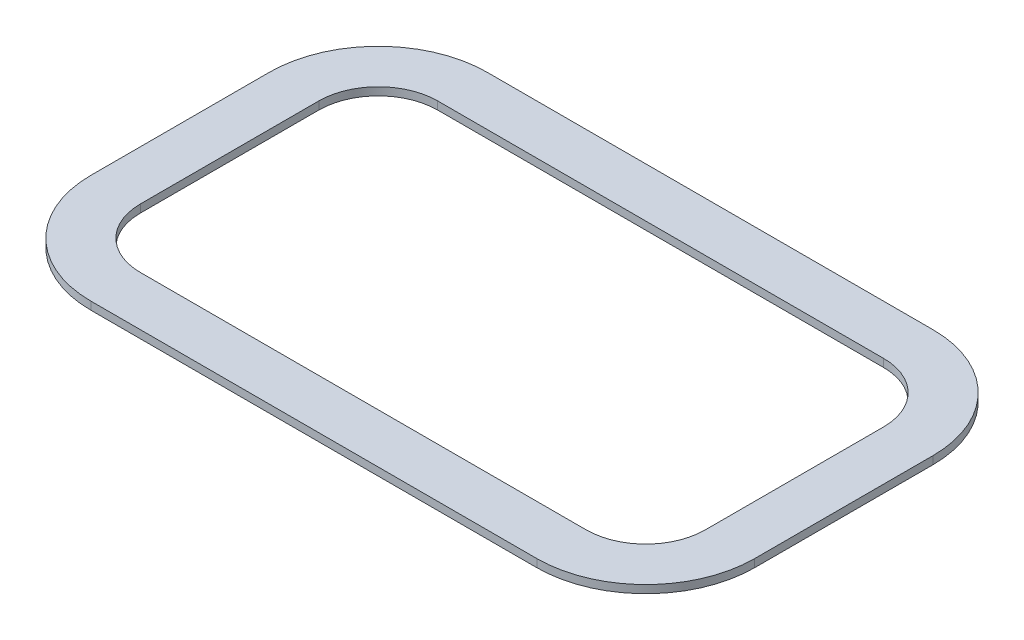
SolidWorks part; units mm, degrees
ref_plane "Front Plane" through (0, 0, 0) normal (0, 0, 1) x (1, 0, 0)
ref_plane "Top Plane" through (0, 0, 0) normal (0, 1, 0) x (1, 0, 0)
ref_plane "Right Plane" through (0, 0, 0) normal (1, 0, 0) x (0, 0, -1)
sketch "Sketch1" plane through (0, 0, 0) normal (0, 1, 0) x (1, 0, 0)
  line L0 (55, 25) -> (280, 25)
  line L1 (55, 0) -> (280, 0)
  line L2 (0, 55) -> (0, 145)
  line L3 (55, 200) -> (280, 200)
  line L4 (335, 55) -> (335, 145)
  line L5 (310, 55) -> (310, 145)
  line L6 (55, 175) -> (280, 175)
  line L7 (25, 55) -> (25, 145)
  arc A0 (55, 0) -> (0, 55) centre (55, 55) cw
  arc A1 (280, 0) -> (335, 55) centre (280, 55) ccw
  arc A2 (280, 200) -> (335, 145) centre (280, 145) cw
  arc A3 (0, 145) -> (55, 200) centre (55, 145) cw
  arc A4 (280, 25) -> (310, 55) centre (280, 55) ccw
  arc A5 (280, 175) -> (310, 145) centre (280, 145) cw
  arc A6 (25, 145) -> (55, 175) centre (55, 145) cw
  arc A7 (55, 25) -> (25, 55) centre (55, 55) cw
  point P7 (0, 0)
  point P12 (335, 200)
  point P15 (0, 200)
  dimension "D3" = 55
  dimension "D1" = 335
  dimension "D2" = 200
  dimension "D4" = 25
extrude "Boss-Extrude1" add sketch "Sketch1" along normal blind 4
